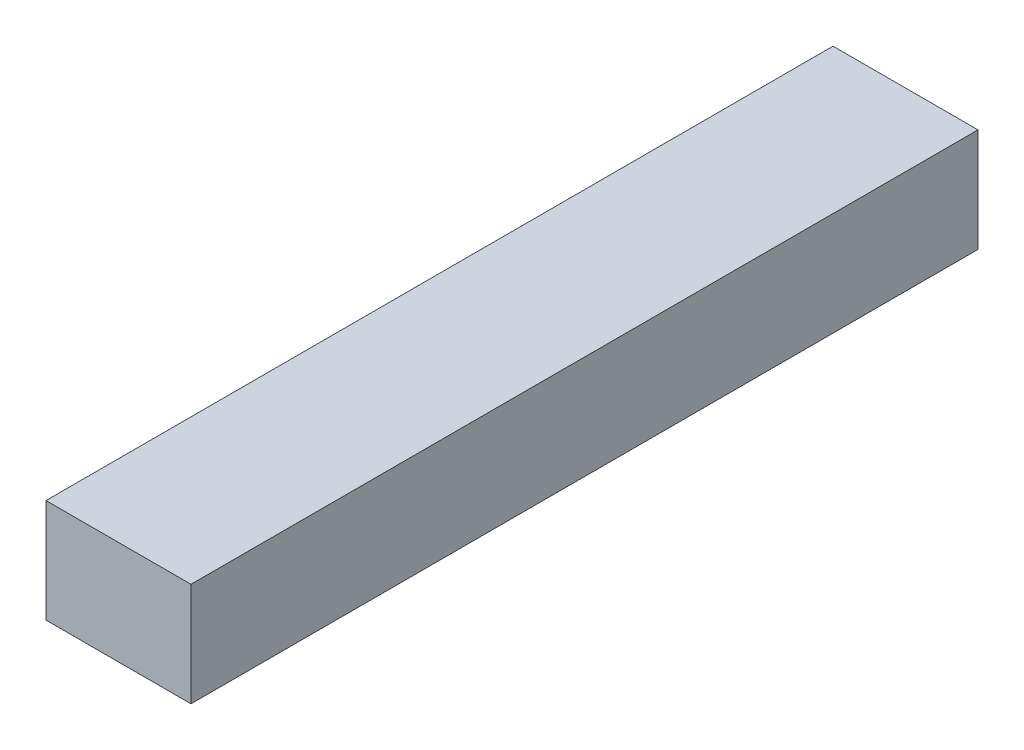
SolidWorks part; units mm, degrees
ref_plane "Front Plane" through (0, 0, 0) normal (0, 0, 1) x (1, 0, 0)
ref_plane "Top Plane" through (0, 0, 0) normal (0, 1, 0) x (1, 0, 0)
ref_plane "Right Plane" through (0, 0, 0) normal (1, 0, 0) x (0, 0, -1)
sketch "Sketch1" plane through (0, 0, 0) normal (0, 0, 1) x (1, 0, 0)
  line L1 (-7, 5) -> (7, 5)
  line L2 (-7, 5) -> (-7, -5)
  line L3 (-7, -5) -> (7, -5)
  line L4 (7, 5) -> (7, -5)
  line L5 (-7, 5) -> (7, -5) construction
  line L6 (-7, -5) -> (7, 5) construction
  point P0 (0, 0)
  dimension "D1" = 14
  dimension "D2" = 10
extrude "Boss-Extrude1" add sketch "Sketch1" along normal mid plane 76
